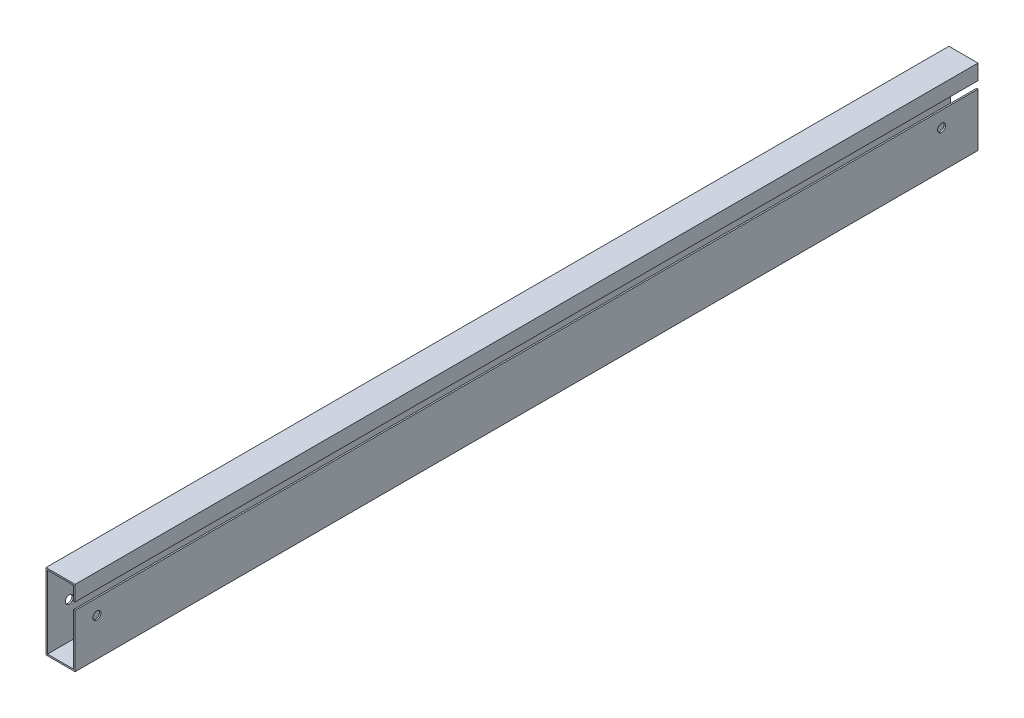
SolidWorks part; units mm, degrees
ref_plane "Front Plane" through (0, 0, 0) normal (0, 0, 1) x (1, 0, 0)
ref_plane "Top Plane" through (0, 0, 0) normal (0, 1, 0) x (1, 0, 0)
ref_plane "Right Plane" through (0, 0, 0) normal (1, 0, 0) x (0, 0, -1)
sketch "Sketch1" plane through (0, 0, 0) normal (0, 0, 1) x (1, 0, 0)
  line L1 (-10, 26) -> (10, 26)
  line L2 (-10, 26) -> (-10, -26)
  line L3 (-10, -26) -> (10, -26)
  line L4 (10, 26) -> (10, -26)
  line L5 (-10, 26) -> (10, -26) construction
  line L6 (-10, -26) -> (10, 26) construction
  point P0 (0, 0)
  point P5 (0, 0)
  dimension "D1" = 52
  dimension "D2" = 20
extrude "Boss-Extrude1" add sketch "Sketch1" against normal blind 620
sketch "Sketch2" plane through (0, 0, 0) normal (0, 0, 1) x (1, 0, 0)
  line L1 (-9, 25) -> (9, 25)
  line L2 (-9, 25) -> (-9, -25)
  line L3 (-9, -25) -> (9, -25)
  line L4 (9, 25) -> (9, -25)
  line L5 (-9, 25) -> (9, -25) construction
  line L6 (-9, -25) -> (9, 25) construction
  point P0 (0, 0)
  point P5 (0, 0)
  dimension "D1" = 18
  dimension "D2" = 50
extrude "Cut-Extrude1" cut sketch "Sketch2" against normal blind 1200
sketch "Sketch4" plane through (10, 0, 0) normal (1, 0, 0) x (0, 0, -1)
  circle A0 centre (15, 0) radius 2.75
  point P2 (0, 0)
  dimension "D2" = 5.5
  dimension "D1" = 15
extrude "Cut-Extrude2" cut sketch "Sketch4" against normal blind 20
sketch "Sketch5" plane through (0, 0, 0) normal (0, 0, 1) x (1, 0, 0)
  line L0 (10, -26) -> (10, 26) construction
  line L1 (9, 15.5) -> (10, 15.5)
  line L2 (9, 15.5) -> (9, 10.5)
  line L3 (9, 10.5) -> (10, 10.5)
  line L4 (10, 15.5) -> (10, 10.5)
  line L5 (9, 15.5) -> (10, 10.5) construction
  line L6 (9, 10.5) -> (10, 15.5) construction
  line L7 (9, -25) -> (9, 25) construction
  line L8 (10, 26) -> (-10, 26) construction
  line L9 (-10, -26) -> (10, -26) construction
  point P0 (9.5, 13)
  point P5 (0, 0)
  point P8 (0, 0)
  dimension "D1" = 13
  dimension "D2" = 5
  dimension "D3" = 39
extrude "Cut-Extrude3" cut sketch "Sketch5" against normal blind 1200
sketch "Sketch6" plane through (10, 0, 0) normal (1, 0, 0) x (0, 0, -1)
  line L0 (620, -26) -> (0, -26) construction
  line L1 (620, -26) -> (620, 10.5) construction
  circle A0 centre (595, 0) radius 2.75
  circle A1 centre (15, 0) radius 2.75 construction
  point P2 (0, 0)
  dimension "D3" = 5.5
  dimension "D4" = 580
  dimension "D1" = 26
  dimension "D2" = 25
extrude "Cut-Extrude4" cut sketch "Sketch6" against normal blind 20
